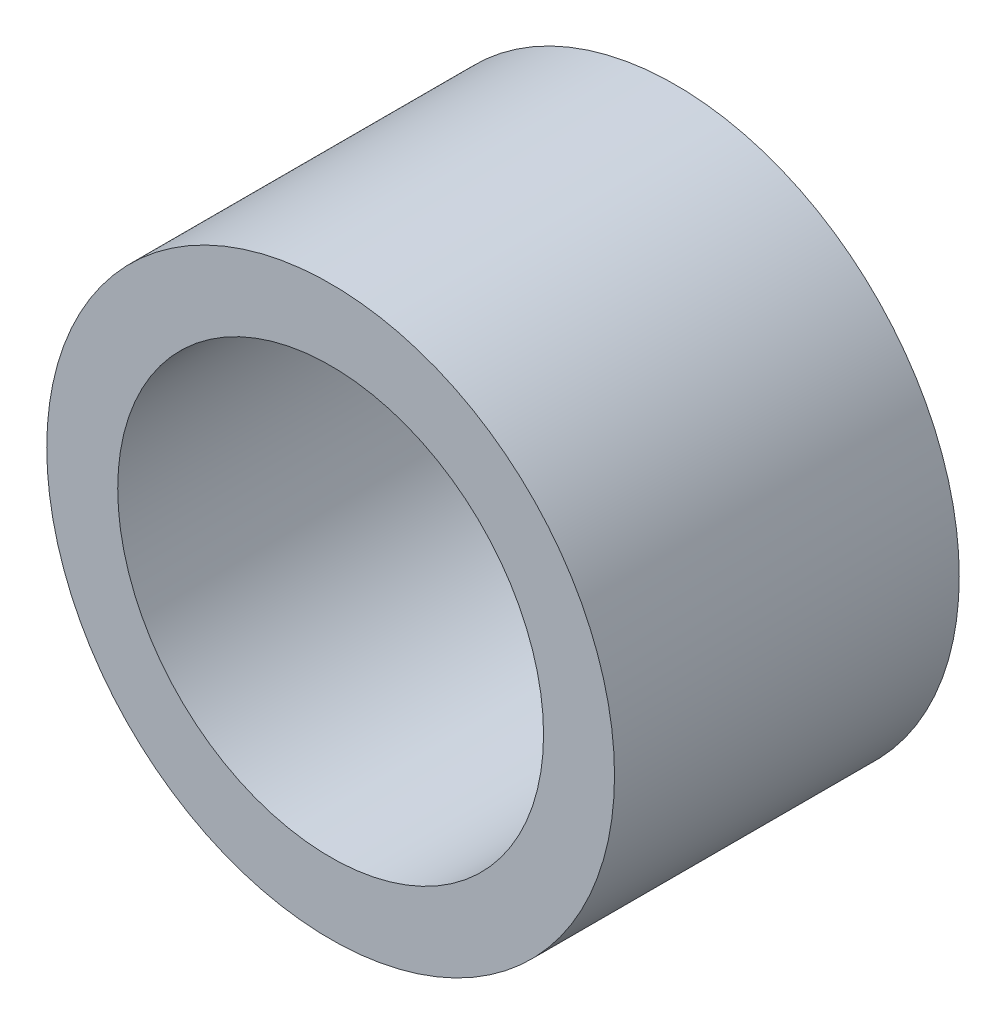
SolidWorks part; units mm, degrees
ref_plane "Front Plane" through (0, 0, 0) normal (0, 0, 1) x (1, 0, 0)
ref_plane "Top Plane" through (0, 0, 0) normal (0, 1, 0) x (1, 0, 0)
ref_plane "Right Plane" through (0, 0, 0) normal (1, 0, 0) x (0, 0, -1)
sketch "Sketch1" plane through (0, 0, 0) normal (0, 0, 1) x (1, 0, 0)
  circle A0 centre (0, 0) radius 7
  circle A1 centre (0, 0) radius 5.25
  dimension "D1" = 10.5
  dimension "D2" = 14
extrude "Boss-Extrude1" add sketch "Sketch1" along normal blind 8.5
